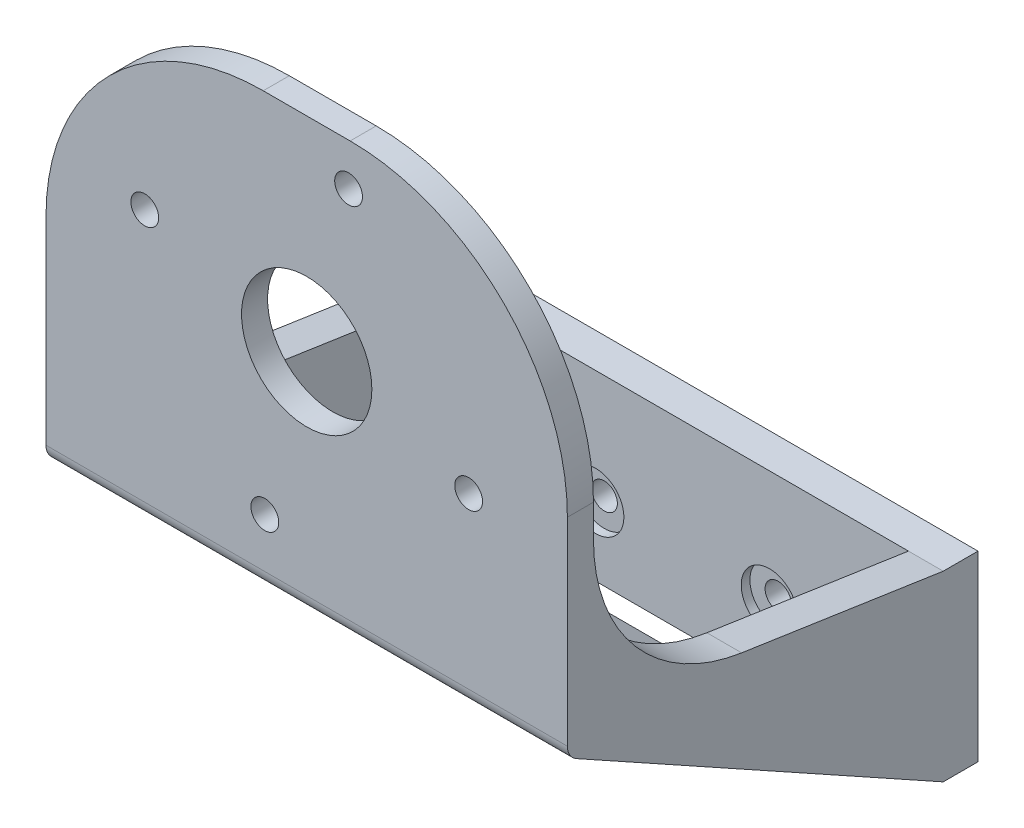
SolidWorks part; units mm, degrees
ref_plane "前视基准面" through (0, 0, 0) normal (0, 0, 1) x (1, 0, 0)
ref_plane "上视基准面" through (0, 0, 0) normal (0, 1, 0) x (1, 0, 0)
ref_plane "右视基准面" through (0, 0, 0) normal (1, 0, 0) x (0, 0, -1)
other "Configuration Table"
sketch "草图1" plane through (0, 0, 0) normal (0, 0, 1) x (1, 0, 0)
  line L0 (10, 0) -> (-10, 0) construction
  line L1 (-30, 5) -> (30, 5)
  line L2 (-30, 5) -> (-30, -5)
  line L3 (-30, -5) -> (30, -5)
  line L4 (30, 5) -> (30, -5)
  line L5 (-30, 5) -> (30, -5) construction
  line L6 (-30, -5) -> (30, 5) construction
  line L7 (-30, 5) -> (30, 5)
  line L8 (-30, 5) -> (-30, 13)
  line L9 (30, 5) -> (30, 13)
  line L10 (-30, 13) -> (30, 13)
  line L11 (-30, -5) -> (30, -5)
  line L12 (-30, -5) -> (-30, -8)
  line L13 (30, -5) -> (30, -8)
  line L14 (-30, -8) -> (30, -8)
  circle A0 centre (-10, 0) radius 1.5
  circle A1 centre (10, 0) radius 1.5
  point P0 (0, 0)
  point P11 (0, 0)
  dimension "D1" = 3
  dimension "D2" = 20
  dimension "D3" = 60
  dimension "D4" = 10
  dimension "D5" = 8
  dimension "D6" = 3
extrude "凸台-拉伸1" add sketch "草图1" along normal blind 4 contours L4 L1 L2 L3 A1 A0 | L10 L8 L1 L9 | L12 L14 L13 L3
sketch "草图3" plane through (0, 0, 4) normal (0, 0, 1) x (1, 0, 0)
  circle A4 centre (-10, 0) radius 3.25
  circle A5 centre (10, 0) radius 3.25
  point P1 (10, 0)
  point P3 (-10, 0)
  dimension "D1" = 6.5
extrude "切除-拉伸1" cut sketch "草图3" against normal blind 1
sketch "草图5" plane through (-30, 0, 0) normal (-1, 0, 0) x (0, 0, 1)
  line L0 (4, 13) -> (44.25, 19)
  line L1 (44.25, 19) -> (44.25, 65)
  line L2 (44.25, 65) -> (47.25, 65)
  line L3 (47.25, 65) -> (47.25, 16)
  line L4 (0, 13) -> (0, -8)
  line L5 (0, -8) -> (4, -8)
  line L6 (4, -8) -> (4, 13)
  line L7 (4, 13) -> (0, 13)
  line L8 (0, 13) -> (0, -8)
  line L10 (4, -8) -> (4, 13)
  line L11 (4, 13) -> (0, 13)
  line L12 (47.25, 16) -> (4, -8)
  line L17 (0, -8) -> (4, -8)
  line M9 (4, -8) -> (4, 13)
  dimension "D2" = 40.25
  dimension "D3" = 6
  dimension "D4" = 3
  dimension "D5" = 3
  dimension "D6" = 46
  dimension "D1" = 0
extrude "凸台-拉伸2" add sketch "草图5" against normal blind 4 contours L12 L3 L2 L1 L0 M9
sketch "草图6" plane through (30, 0, 0) normal (1, 0, 0) x (0, 0, -1)
  line L4 (0, -8) -> (0, 13)
  line L5 (0, 13) -> (-4, 13)
  line L6 (-4, 13) -> (-4, -8)
  line L7 (-4, -8) -> (0, -8)
  line L8 (0, -8) -> (0, 13)
  line L9 (0, 13) -> (-4, 13)
  line L10 (-4, 13) -> (-4, -8)
  line L14 (-47.25, 16) -> (-4, -8)
  line L15 (-4, -8) -> (-4, 13)
  line L16 (-4, 13) -> (-44.25, 19)
  line L17 (-44.25, 19) -> (-44.25, 65)
  line L18 (-44.25, 65) -> (-47.25, 65)
  line L19 (-47.25, 65) -> (-47.25, 16)
  line L20 (-47.25, 16) -> (-4, -8)
  line L21 (-4, -8) -> (-4, 13)
  line L22 (-4, 13) -> (-44.25, 19)
  line L23 (-44.25, 19) -> (-44.25, 65)
  line L24 (-44.25, 65) -> (-47.25, 65)
  line L25 (-47.25, 65) -> (-47.25, 16)
  line L26 (-4, -8) -> (0, -8)
  line M13 (-4, 13) -> (-4, -8)
  dimension "D1" = 0
  dimension "D2" = 0
extrude "凸台-拉伸3" add sketch "草图6" against normal blind 4 contours L24 L25 L20 L22 L23 M13
sketch "草图7" plane through (-26, 0, 0) normal (1, 0, 0) x (0, 0, -1)
  line L0 (-44.25, 19) -> (-44.25, 14.3353)
  line L6 (-47.25, 16) -> (-4, -8)
  line L7 (-4, -8) -> (-4, 13)
  line L8 (-4, 13) -> (-44.25, 19)
  line L9 (-44.25, 19) -> (-44.25, 65)
  line L10 (-44.25, 65) -> (-47.25, 65)
  line L11 (-47.25, 65) -> (-47.25, 16)
  line L12 (-47.25, 16) -> (-4, -8)
  line L13 (-4, -8) -> (-4, 13)
  line L14 (-4, 13) -> (-44.25, 19)
  line L15 (-44.25, 19) -> (-44.25, 65)
  line L16 (-44.25, 65) -> (-47.25, 65)
  line L17 (-47.25, 65) -> (-47.25, 16)
  line M7 (-47.25, 16) -> (-4, -8)
  line M10 (-44.25, 19) -> (-44.25, 65)
  line M11 (-44.25, 65) -> (-47.25, 65)
  line M12 (-47.25, 65) -> (-47.25, 16)
  dimension "D1" = 0
extrude "凸台-拉伸4" add sketch "草图7" along normal up to surface (52 mm away) contours L0 M10 M11 M12 M7 up to face at (26, 28.3333, 31.8333)
fillet "圆角1" radius 25 2 edges at (-30, 65, 45.75) (30, 65, 45.75)
fillet "圆角2" radius 20 2 edges at (28, 19, 44.25) (-28, 19, 44.25)
sketch "草图9" plane through (-26, 0, 0) normal (1, 0, 0) x (0, 0, -1)
  line L0 (-34.6038, 8.9825) -> (-17.1159, -0.7218)
  line L1 (-34.6038, 8.9825) -> (-33.1482, 11.6057)
  line L2 (-17.1159, -0.7218) -> (-15.6603, 1.9014)
  line L3 (-33.1482, 11.6057) -> (-15.6603, 1.9014)
  line L4 (-4, 13) -> (-27.1988, 16.4582)
  line L5 (-44.25, 36.2396) -> (-44.25, 14.3353)
  line L6 (-44.25, 14.3353) -> (-4, -8)
  line L7 (-4, -8) -> (-4, 13)
  line L8 (-4, 13) -> (-27.1988, 16.4582)
  line L9 (-44.25, 36.2396) -> (-44.25, 14.3353)
  line L10 (-44.25, 14.3353) -> (-4, -8)
  line L11 (-4, -8) -> (-4, 13)
  line L12 (-17.1159, -0.7218) -> (-17.1159, 2.7091)
  arc A1 (-44.25, 36.2396) -> (-27.1988, 16.4582) centre (-24.25, 36.2396) ccw
  arc A2 (-44.25, 36.2396) -> (-27.1988, 16.4582) centre (-24.25, 36.2396) ccw
  line M12 (-44.25, 14.3353) -> (-4, -8)
  dimension "D2" = 3
  dimension "D3" = 15
  dimension "D4" = 20
  dimension "D1" = 0
extrude "凸台-拉伸6" add sketch "草图9" along normal up to surface (52 mm away) contours L3 L1 L2 M12
fillet "圆角4" radius 6 2 edges at (26, 10.2941, 33.876) (-26, 10.2941, 33.876)
fillet "圆角5" radius 2 1 edges at (0, -0.7218, 17.1159)
sketch "草图11" plane through (0, 0, 47.25) normal (0, 0, 1) x (1, 0, 0)
  arc A4 (-4.2075, 24.3414) -> (-5.4321, 21.385) centre (-4.8198, 22.8632) ccw construction
  arc A5 (-5.4321, 21.385) -> (-4.2075, 24.3414) centre (-4.8198, 22.8632) ccw construction
  arc A6 (-4.2075, 24.3414) -> (-5.4321, 21.385) centre (-4.8198, 22.8632) ccw
  arc A7 (-5.4321, 21.385) -> (-4.2075, 24.3414) centre (-4.8198, 22.8632) ccw
  arc A8 (20.2775, 31.2965) -> (12.7884, 60.2549) centre (0, 41.5) ccw construction
  arc A9 (20.2775, 31.2965) -> (12.7884, 60.2549) centre (0, 41.5) ccw
  arc A10 (-20.115, 46.9321) -> (-17.1586, 45.7075) centre (-18.6368, 46.3198) ccw
  arc A11 (-17.1586, 45.7075) -> (-20.115, 46.9321) centre (-18.6368, 46.3198) ccw
  arc A12 (5.4321, 61.615) -> (4.2075, 58.6586) centre (4.8198, 60.1368) ccw
  arc A13 (4.2075, 58.6586) -> (5.4321, 61.615) centre (4.8198, 60.1368) ccw
  arc A14 (20.115, 36.0679) -> (17.1586, 37.2925) centre (18.6368, 36.6802) ccw
  arc A15 (17.1586, 37.2925) -> (20.115, 36.0679) centre (18.6368, 36.6802) ccw
  circle A16 centre (0, 41.5) radius 7.5
  point P18 (0, 41.5)
  dimension "D2" = 15
  dimension "D1" = 4
extrude "切除-拉伸2" cut sketch "草图11" against normal blind 4 contours A10 A11 | A6 A7 | A14 A15 | A12 A13 | A16
fillet "圆角6" radius 2 1 edges at (0, 16, 47.25)
